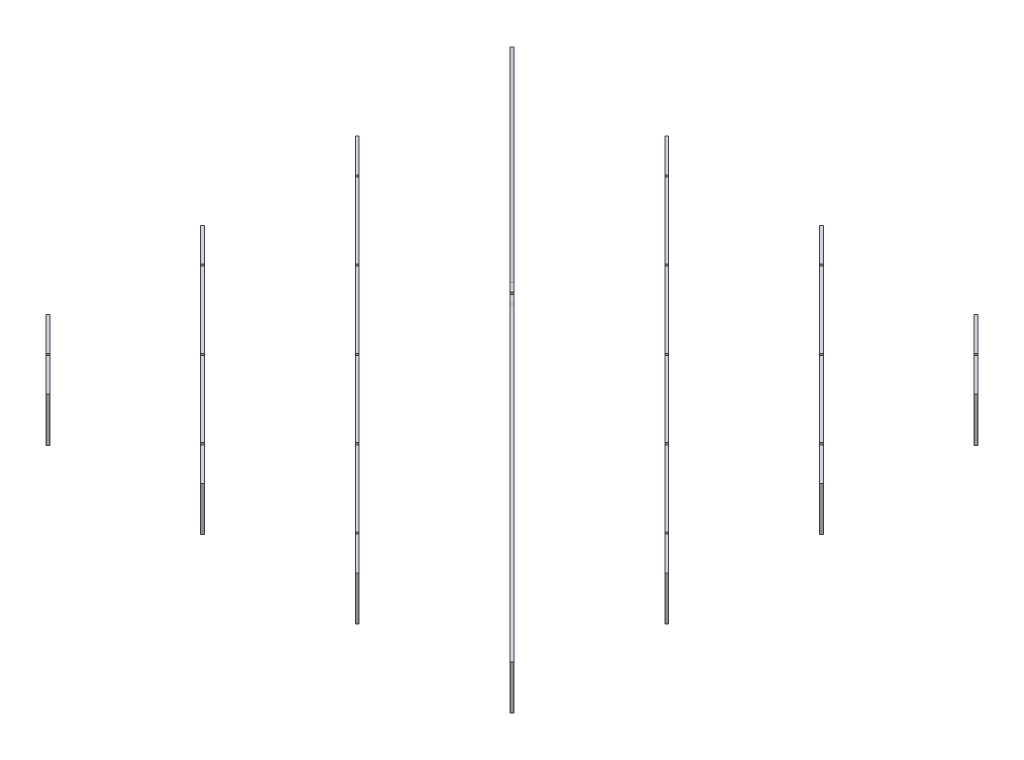
SolidWorks part; units mm, degrees
material "Plain Carbon Steel"
ref_plane "Front" through (0, 0, 0) normal (0, 0, 1) x (1, 0, 0)
ref_plane "Top" through (0, 0, 0) normal (0, 1, 0) x (1, 0, 0)
ref_plane "Right" through (0, 0, 0) normal (1, 0, 0) x (0, 0, -1)
sketch "Sketch1" plane through (0, 0, 0) normal (0, 1, 0) x (1, 0, 0)
  line L0 (-525, -525) -> (-525, 525) construction
  line L1 (-605, 605) -> (605, 605) construction
  line L2 (-605, 605) -> (-605, -605) construction
  line L3 (-605, -605) -> (605, -605) construction
  line L4 (605, 605) -> (605, -605) construction
  line L5 (-605, 605) -> (605, -605) construction
  line L6 (-605, -605) -> (605, 605) construction
  line L7 (-525, 525) -> (525, 525) construction
  line L8 (-525, 350) -> (525, 350) construction
  line L9 (-525, 175) -> (525, 175) construction
  line L10 (-525, 0) -> (525, 0) construction
  line L11 (-525, -175) -> (525, -175) construction
  line L12 (-525, -350) -> (525, -350) construction
  line L13 (-525, -525) -> (525, -525) construction
  line L14 (-350, -525) -> (-350, 525) construction
  line L15 (-175, -525) -> (-175, 525) construction
  line L16 (0, -525) -> (0, 525) construction
  line L17 (175, -525) -> (175, 525) construction
  line L18 (350, -525) -> (350, 525) construction
  line L19 (525, -525) -> (525, 525) construction
  point P0 (0, 0)
  dimension "D1" = 1210
  dimension "D2" = 1210
  dimension "D5" = 175
  dimension "D3" = 7
  dimension "D4" = 7
sketch "Sketch2" plane through (0, 0, 0) normal (0, 1, 0) x (1, 0, 0)
  line L0 (-605, 605) -> (605, -605) construction
  line L1 (602.8787, -602.8787) -> (-602.8787, -602.8787) construction
  line L2 (602.8787, -602.8787) -> (602.8787, 602.8787) construction
  line L3 (602.8787, 602.8787) -> (-602.8787, 602.8787) construction
  line L4 (-602.8787, -602.8787) -> (-602.8787, 602.8787) construction
  line L5 (602.8787, -602.8787) -> (-602.8787, 602.8787) construction
  line L6 (602.8787, 602.8787) -> (-602.8787, -602.8787) construction
  line L7 (-252.8787, 602.8787) -> (602.8787, -252.8787) construction
  line L8 (97.1213, 602.8787) -> (602.8787, 97.1213) construction
  line L9 (447.1213, 602.8787) -> (602.8787, 447.1213) construction
  line L10 (-602.8787, 252.8787) -> (252.8787, -602.8787) construction
  line L11 (-602.8787, -97.1213) -> (-97.1213, -602.8787) construction
  line L12 (-602.8787, -447.1213) -> (-447.1213, -602.8787) construction
  line L13 (-605, -449.2426) -> (-449.2426, -605)
  line L14 (-605, -99.2426) -> (-99.2426, -605)
  line L15 (-605, 250.7574) -> (250.7574, -605)
  line L16 (605, -600.7574) -> (-600.7574, 605)
  line L17 (-255, 600.7574) -> (600.7574, -255)
  line L18 (95, 600.7574) -> (600.7574, 95)
  line L19 (445, 600.7574) -> (600.7574, 445)
  line L20 (-600.7574, -445) -> (-445, -600.7574)
  line L21 (-600.7574, -95) -> (-95, -600.7574)
  line L22 (-600.7574, 255) -> (255, -600.7574)
  line L23 (600.7574, -605) -> (-605, 600.7574)
  line L24 (-250.7574, 605) -> (605, -250.7574)
  line L25 (99.2426, 605) -> (605, 99.2426)
  line L26 (449.2426, 605) -> (605, 449.2426)
  line L27 (-605, 605) -> (605, 605) construction
  line L29 (-605, -449.2426) -> (-600.7574, -445)
  line L30 (-449.2426, -605) -> (-445, -600.7574)
  line L31 (-605, -99.2426) -> (-600.7574, -95)
  line L32 (-99.2426, -605) -> (-95, -600.7574)
  line L33 (-605, 250.7574) -> (-600.7574, 255)
  line L34 (250.7574, -605) -> (255, -600.7574)
  line L35 (605, -600.7574) -> (600.7574, -605)
  line L36 (-600.7574, 605) -> (-605, 600.7574)
  line L37 (-255, 600.7574) -> (-250.7574, 605)
  line L38 (600.7574, -255) -> (605, -250.7574)
  line L39 (95, 600.7574) -> (99.2426, 605)
  line L40 (600.7574, 95) -> (605, 99.2426)
  line L41 (445, 600.7574) -> (449.2426, 605)
  line L42 (600.7574, 445) -> (605, 449.2426)
  point P0 (0, 0)
extrude "Boss-Extrude1" add sketch "Sketch2" along normal blind 100
sketch "Sketch4" plane through (-2.1213, 0, 2.1213) normal (-0.7071, 0, 0.7071) x (0.7071, 0, 0.7071)
  line L0 (0, 100) -> (0, 220) construction
  line L1 (-110.1371, 100) -> (110.1371, 100) construction
  line L2 (-30, 220) -> (-852.5992, 100)
  line L3 (-852.5992, 100) -> (-30, 100)
  line L4 (-30, 100) -> (-30, 220) construction
  line L5 (30, 220) -> (-30, 220)
  line L6 (852.5992, 100) -> (30, 100)
  line L7 (30, 220) -> (852.5992, 100)
  line L8 (-30, 100) -> (30, 100)
  dimension "D1" = 120
  dimension "D2" = 30
extrude "Boss-Extrude2" add sketch "Sketch4" against normal up to vertex
sketch "Sketch5" plane through (-527.1213, 0, 527.1213) normal (-0.7071, 0, 0.7071) x (0.7071, 0, 0.7071)
  line L0 (0, 0) -> (0, 100) construction
  line L1 (-110.1371, 100) -> (110.1371, 100) construction
  line L2 (-247.4874, 0) -> (-247.4874, 100) construction
  line L3 (494.9747, 0) -> (-247.4874, 0) construction
  line L4 (-742.4621, 0) -> (0, 0) construction
  line L5 (-357.6245, 100) -> (357.6245, 100) construction
  line L6 (-494.9747, 0) -> (-494.9747, 100) construction
  line L7 (247.4874, 0) -> (-494.9747, 0) construction
  line L8 (123.7437, 0) -> (-618.7184, 0) construction
  line L9 (-605.1118, 100) -> (605.1118, 100) construction
  line L10 (497.9747, 50) -> (491.9747, 150) construction
  line L11 (-250.4874, 150) -> (-244.4874, 150)
  line L12 (-250.4874, 150) -> (-250.4874, 50)
  line L13 (-250.4874, 50) -> (-244.4874, 50)
  line L14 (-244.4874, 150) -> (-244.4874, 50)
  line L15 (-250.4874, 150) -> (-244.4874, 50) construction
  line L16 (-250.4874, 50) -> (-244.4874, 150) construction
  line L17 (-497.9747, 150) -> (-491.9747, 150)
  line L18 (-497.9747, 150) -> (-497.9747, 50)
  line L19 (-497.9747, 50) -> (-491.9747, 50)
  line L20 (-491.9747, 150) -> (-491.9747, 50)
  line L21 (-497.9747, 150) -> (-491.9747, 50) construction
  line L22 (-497.9747, 50) -> (-491.9747, 150) construction
  line L23 (-3, 150) -> (3, 150)
  line L24 (-3, 150) -> (-3, 50)
  line L25 (-3, 50) -> (3, 50)
  line L26 (3, 150) -> (3, 50)
  line L27 (-3, 150) -> (3, 50) construction
  line L28 (-3, 50) -> (3, 150) construction
  line L29 (497.9747, 150) -> (491.9747, 50) construction
  line L30 (250.4874, 50) -> (244.4874, 150) construction
  line L31 (250.4874, 150) -> (244.4874, 50) construction
  line L32 (494.9747, 0) -> (494.9747, 100) construction
  line L33 (247.4874, 0) -> (247.4874, 100) construction
  line L34 (491.9747, 150) -> (491.9747, 50)
  line L35 (497.9747, 50) -> (491.9747, 50)
  line L36 (497.9747, 150) -> (497.9747, 50)
  line L37 (497.9747, 150) -> (491.9747, 150)
  line L38 (244.4874, 150) -> (244.4874, 50)
  line L39 (250.4874, 50) -> (244.4874, 50)
  line L40 (250.4874, 150) -> (250.4874, 50)
  line L41 (250.4874, 150) -> (244.4874, 150)
  circle A0 centre (-497.9747, 50) radius 1.5
  circle A1 centre (-491.9747, 50) radius 1.5
  circle A2 centre (-250.4874, 50) radius 1.5
  circle A3 centre (-244.4874, 50) radius 1.5
  circle A4 centre (-3, 50) radius 1.5
  circle A5 centre (3, 50) radius 1.5
  circle A6 centre (244.4874, 50) radius 1.5
  circle A7 centre (250.4874, 50) radius 1.5
  circle A8 centre (491.9747, 50) radius 1.5
  circle A9 centre (497.9747, 50) radius 1.5
  line M11 (110.1371, 100) -> (-110.1371, 100)
  dimension "D7" = 3
  dimension "D8" = 3
  dimension "D9" = 3
  dimension "D10" = 3
  dimension "D11" = 3
  dimension "D12" = 3
  dimension "D1" = 3
  dimension "D2" = 3
  dimension "D3" = 3
  dimension "D4" = 100
  dimension "D5" = 100
  dimension "D6" = 100
extrude "Cut-Extrude1" cut sketch "Sketch5" against normal up to surface (500.9747 mm away) contours L35 A9 L36 L37 L34 A8 | A8 L34 L35 | A8 L35 L34 | A9 L36 L35 | A9 L35 L36 | L39 A7 L40 L41 L38 A6 | A6 L38 L39 | A6 L39 L38 | A7 L39 L40 | A7 L40 L39 | A5 L26 L24 A4 L25 M11 | L25 A4 L24 | L24 A4 L25 | L26 A5 L25 | L25 A5 L26 | A3 L14 L11 L12 A2 L13 | L13 A2 L12 | L12 A2 L13 | L14 A3 L13 | L13 A3 L14 | A1 L20 L17 L18 A0 L19 | L19 A0 L18 | L18 A0 L19 | L20 A1 L19 | L19 A1 L20 up to face at (-172.8787, 50, 172.8787)
sketch "Sketch6" plane through (527.1213, 0, -527.1213) normal (0.7071, 0, -0.7071) x (-0.7071, 0, -0.7071)
  line L4 (-110.1371, 0) -> (110.1371, 0)
  line L5 (110.1371, 0) -> (110.1371, 100)
  line L6 (110.1371, 100) -> (-110.1371, 100)
  line L7 (-110.1371, 100) -> (-110.1371, 0)
  line L8 (-110.1371, 0) -> (110.1371, 0)
  line L9 (110.1371, 0) -> (110.1371, 100)
  line L10 (110.1371, 100) -> (-110.1371, 100)
  line L11 (-110.1371, 100) -> (-110.1371, 0)
  line L12 (497.9747, 150) -> (491.9747, 150)
  line L13 (491.9747, 150) -> (491.9747, 50)
  line L14 (491.9747, 50) -> (497.9747, 50)
  line L15 (497.9747, 50) -> (497.9747, 150)
  line L16 (497.9747, 150) -> (491.9747, 150)
  line L17 (491.9747, 150) -> (491.9747, 50)
  line L18 (491.9747, 50) -> (497.9747, 50)
  line L19 (497.9747, 50) -> (497.9747, 150)
  line L20 (250.4874, 150) -> (244.4874, 150)
  line L21 (244.4874, 150) -> (244.4874, 50)
  line L22 (244.4874, 50) -> (250.4874, 50)
  line L23 (250.4874, 50) -> (250.4874, 150)
  line L24 (250.4874, 150) -> (244.4874, 150)
  line L25 (244.4874, 150) -> (244.4874, 50)
  line L26 (244.4874, 50) -> (250.4874, 50)
  line L27 (250.4874, 50) -> (250.4874, 150)
  line L28 (-244.4874, 50) -> (-244.4874, 150)
  line L29 (-250.4874, 50) -> (-244.4874, 50)
  line L30 (-250.4874, 150) -> (-250.4874, 50)
  line L31 (-244.4874, 150) -> (-250.4874, 150)
  line L32 (-244.4874, 50) -> (-244.4874, 150)
  line L33 (-250.4874, 50) -> (-244.4874, 50)
  line L34 (-250.4874, 150) -> (-250.4874, 50)
  line L35 (-244.4874, 150) -> (-250.4874, 150)
  line L36 (-491.9747, 50) -> (-491.9747, 150)
  line L37 (-497.9747, 50) -> (-491.9747, 50)
  line L38 (-497.9747, 150) -> (-497.9747, 50)
  line L39 (-491.9747, 150) -> (-497.9747, 150)
  line L40 (-491.9747, 50) -> (-491.9747, 150)
  line L41 (-497.9747, 50) -> (-491.9747, 50)
  line L42 (-497.9747, 150) -> (-497.9747, 50)
  line L43 (-491.9747, 150) -> (-497.9747, 150)
  line L44 (3, 150) -> (-3, 150)
  line L45 (3, 50) -> (3, 150)
  line L46 (-3, 50) -> (3, 50)
  line L47 (-3, 150) -> (-3, 50)
  line L48 (3, 150) -> (-3, 150)
  line L49 (3, 50) -> (3, 150)
  line L50 (-3, 50) -> (3, 50)
  line L51 (-3, 150) -> (-3, 50)
  circle A1 centre (-3, 50) radius 1.5
  circle A2 centre (-3, 50) radius 1.5
  circle A3 centre (3, 50) radius 1.5
  circle A4 centre (3, 50) radius 1.5
  circle A5 centre (244.4874, 50) radius 1.5
  circle A6 centre (244.4874, 50) radius 1.5
  circle A7 centre (250.4874, 50) radius 1.5
  circle A8 centre (250.4874, 50) radius 1.5
  circle A9 centre (491.9747, 50) radius 1.5
  circle A10 centre (491.9747, 50) radius 1.5
  circle A11 centre (497.9747, 50) radius 1.5
  circle A12 centre (497.9747, 50) radius 1.5
  circle A13 centre (-497.9747, 50) radius 1.5
  circle A14 centre (-497.9747, 50) radius 1.5
  circle A15 centre (-491.9747, 50) radius 1.5
  circle A16 centre (-491.9747, 50) radius 1.5
  circle A17 centre (-250.4874, 50) radius 1.5
  circle A18 centre (-250.4874, 50) radius 1.5
  circle A19 centre (-244.4874, 50) radius 1.5
  circle A20 centre (-244.4874, 50) radius 1.5
  dimension "D1" = 0
  dimension "D2" = 0
  dimension "D3" = 0
  dimension "D4" = 0
  dimension "D5" = 0
  dimension "D6" = 0
  dimension "D7" = 0
  dimension "D8" = 0
  dimension "D9" = 0
  dimension "D10" = 0
  dimension "D11" = 0
  dimension "D12" = 0
  dimension "D13" = 0
  dimension "D14" = 0
  dimension "D15" = 0
  dimension "D16" = 0
extrude "Cut-Extrude2" cut sketch "Sketch6" against normal up to surface (500.9747 mm away) contours A16 L40 L43 L42 A14 L41 | L41 A14 L42 | L42 A14 L41 | L40 A16 L41 | L41 A16 L40 | A20 L32 L35 L34 A18 L33 | L33 A18 L34 | L34 A18 L33 | L32 A20 L33 | L33 A20 L32 | A4 L49 L10 L51 A2 L50 | L49 A4 L50 | L50 A4 L49 | L50 A2 L51 | L51 A2 L50 | L25 A6 L26 | L26 A6 L25 | A8 L27 L24 L25 A6 L26 | L27 A8 L26 | L26 A8 L27 | L17 A10 L18 | L18 A10 L17 | A12 L19 L16 L17 A10 L18 | L19 A12 L18 | L18 A12 L19 up to face at (172.8787, 50, -172.8787)
sketch "Sketch7" plane through (-2.1213, 0, 2.1213) normal (-0.7071, 0, 0.7071) x (0.7071, 0, 0.7071)
  line L0 (0, 220) -> (0, 0) construction
  line L1 (30, 220) -> (-30, 220) construction
  line L2 (123.7437, 0) -> (-618.7184, 0) construction
  line L3 (-3, 330) -> (3, 330)
  line L4 (-3, 330) -> (-3, 110)
  line L5 (-3, 110) -> (3, 110)
  line L6 (3, 330) -> (3, 110)
  line L7 (-3, 330) -> (3, 110) construction
  line L8 (-3, 110) -> (3, 330) construction
  line L9 (-250.4874, 50) -> (-244.4874, 50)
  line L10 (-250.4874, 50) -> (-250.4874, -50)
  line L11 (-250.4874, -50) -> (-244.4874, -50)
  line L12 (-244.4874, 50) -> (-244.4874, -50)
  line L13 (-250.4874, 50) -> (-244.4874, -50) construction
  line L14 (-250.4874, -50) -> (-244.4874, 50) construction
  line L15 (247.4874, 0) -> (-494.9747, 0) construction
  line L16 (-497.9747, 50) -> (-491.9747, 50)
  line L17 (-497.9747, 50) -> (-497.9747, -50)
  line L18 (-497.9747, -50) -> (-491.9747, -50)
  line L19 (-491.9747, 50) -> (-491.9747, -50)
  line L20 (-497.9747, 50) -> (-491.9747, -50) construction
  line L21 (-497.9747, -50) -> (-491.9747, 50) construction
  line L22 (-855.5992, 0) -> (855.5992, 0) construction
  line L23 (-742.4621, 0) -> (0, 0) construction
  line L24 (-745.4621, 50) -> (-739.4621, 50)
  line L25 (-745.4621, 50) -> (-745.4621, -50)
  line L26 (-745.4621, -50) -> (-739.4621, -50)
  line L27 (-739.4621, 50) -> (-739.4621, -50)
  line L28 (-745.4621, 50) -> (-739.4621, -50) construction
  line L29 (-745.4621, -50) -> (-739.4621, 50) construction
  line L30 (745.4621, -50) -> (739.4621, 50) construction
  line L31 (745.4621, 50) -> (739.4621, -50) construction
  line L32 (497.9747, -50) -> (491.9747, 50) construction
  line L33 (497.9747, 50) -> (491.9747, -50) construction
  line L34 (250.4874, -50) -> (244.4874, 50) construction
  line L35 (250.4874, 50) -> (244.4874, -50) construction
  line L36 (739.4621, 50) -> (739.4621, -50)
  line L37 (745.4621, -50) -> (739.4621, -50)
  line L38 (745.4621, 50) -> (745.4621, -50)
  line L39 (745.4621, 50) -> (739.4621, 50)
  line L40 (491.9747, 50) -> (491.9747, -50)
  line L41 (497.9747, -50) -> (491.9747, -50)
  line L42 (497.9747, 50) -> (497.9747, -50)
  line L43 (497.9747, 50) -> (491.9747, 50)
  line L44 (244.4874, 50) -> (244.4874, -50)
  line L45 (250.4874, -50) -> (244.4874, -50)
  line L46 (250.4874, 50) -> (250.4874, -50)
  line L47 (250.4874, 50) -> (244.4874, 50)
  circle A0 centre (-3, 110) radius 1.5
  circle A1 centre (3, 110) radius 1.5
  circle A2 centre (-250.4874, 50) radius 1.5
  circle A3 centre (-244.4874, 50) radius 1.5
  circle A4 centre (-491.9747, 50) radius 1.5
  circle A5 centre (-497.9747, 50) radius 1.5
  circle A6 centre (-739.4621, 50) radius 1.5
  circle A7 centre (-745.4621, 50) radius 1.5
  circle A8 centre (745.4621, 50) radius 1.5
  circle A9 centre (739.4621, 50) radius 1.5
  circle A10 centre (497.9747, 50) radius 1.5
  circle A11 centre (491.9747, 50) radius 1.5
  circle A12 centre (244.4874, 50) radius 1.5
  circle A13 centre (250.4874, 50) radius 1.5
  point P9 (-247.4874, 0)
  point P16 (-494.9747, 0)
  point P25 (-742.4621, 0)
  point P32 (0, 110)
  point P59 (742.4621, 0)
  point P60 (494.9747, 0)
  point P61 (247.4874, 0)
  line M15 (-852.5992, 0) -> (852.5992, 0)
  line M18 (30, 220) -> (-30, 220)
  dimension "D7" = 3
  dimension "D8" = 3
  dimension "D9" = 3
  dimension "D10" = 3
  dimension "D11" = 3
  dimension "D12" = 3
  dimension "D1" = 3
  dimension "D3" = 3
  dimension "D4" = 100
  dimension "D6" = 100
  dimension "D13" = 3
  dimension "D14" = 3
  dimension "D15" = 3
  dimension "D2" = 100
  dimension "D5" = 3
extrude "Cut-Extrude3" cut sketch "Sketch7" against normal up to next (6 mm away) contours L24 A7 L25 | L25 A7 L24 | A7 L25 L27 A6 L24 M15 | L24 A6 L27 | L27 A6 L24 | L16 A5 L17 | L17 A5 L16 | A5 L17 L19 A4 L16 M15 | L16 A4 L19 | L19 A4 L16 | L12 A3 L9 | L9 A3 L12 | A3 L9 A2 L10 L12 M15 | L10 A2 L9 | L9 A2 L10 | A1 L6 L4 A0 L5 M18 | L5 A0 L4 | L4 A0 L5 | L5 A1 L6 | L6 A1 L5 | A12 L44 L47 | A12 L47 L44 | L46 A13 L47 A12 L44 M15 | A13 L46 L47 | A13 L47 L46 | A11 L40 L43 | A11 L43 L40 | L43 A11 L40 L42 A10 M15 | A10 L42 L43 | A10 L43 L42 | A9 L36 L39 | A9 L39 L36 | L39 A9 L36 L38 A8 M15 | A8 L38 L39 | A8 L39 L38
sketch "Sketch8" plane through (-2.1213, 0, 2.1213) normal (-0.7071, 0, 0.7071) x (0.7071, 0, 0.7071)
  line L0 (346.2311, 22) -> (396.2311, 22) construction
  line L1 (346.2311, 19) -> (346.2311, 25) construction
  line L2 (396.2311, 25) -> (396.2311, 19) construction
  line L3 (371.2311, 25) -> (371.2311, 19) construction
  line L4 (386.2311, 25) -> (356.2311, 25) construction
  line L5 (356.2311, 19) -> (386.2311, 19) construction
  line L6 (0, 0) -> (0, 262.5502) construction
  line L7 (343.2311, 28) -> (399.2311, 28)
  line L8 (343.2311, 28) -> (343.2311, 16)
  line L9 (343.2311, 16) -> (399.2311, 16)
  line L10 (399.2311, 28) -> (399.2311, 16)
  line L11 (343.2311, 28) -> (399.2311, 16) construction
  line L12 (343.2311, 16) -> (399.2311, 28) construction
  line L13 (-343.2311, 16) -> (-399.2311, 28) construction
  line L14 (-343.2311, 28) -> (-399.2311, 16) construction
  line L15 (-371.2311, 25) -> (-371.2311, 19) construction
  line L16 (-346.2311, 22) -> (-396.2311, 22) construction
  line L17 (-399.2311, 28) -> (-399.2311, 16)
  line L18 (-343.2311, 16) -> (-399.2311, 16)
  line L19 (-343.2311, 28) -> (-343.2311, 16)
  line L20 (-343.2311, 28) -> (-399.2311, 28)
  point P12 (371.2311, 22)
  point P28 (-371.2311, 22)
  dimension "D1" = 3
  dimension "D2" = 3
extrude "Cut-Extrude4" cut sketch "Sketch8" against normal up to next (6 mm away)
sketch "Sketch9" plane through (2.1213, 0, -2.1213) normal (0.7071, 0, -0.7071) x (-0.7071, 0, -0.7071)
  line L0 (123.7437, 74) -> (-123.7437, 74) construction
  line L1 (0, 0) -> (0, 292.3791) construction
  circle A0 centre (123.7437, 64) radius 4
  circle A1 centre (123.7437, 84) radius 4
  circle A2 centre (40, 74) radius 10
  circle A3 centre (-40, 74) radius 10
  circle A4 centre (-123.7437, 84) radius 4
  circle A5 centre (-123.7437, 64) radius 4
  dimension "D1" = 8
  dimension "D2" = 20
  dimension "D3" = 80
extrude "Cut-Extrude5" cut sketch "Sketch9" against normal up to next (6 mm away)
sketch "Sketch10" plane through (177.1213, 0, -177.1213) normal (0.7071, 0, -0.7071) x (-0.7071, 0, -0.7071)
  line L0 (371.2311, 100) -> (371.2311, 0) construction
  line L1 (250.4874, 100) -> (491.9747, 100) construction
  line L2 (-605.1118, 0) -> (605.1118, 0) construction
  line L3 (123.7437, 100) -> (123.7437, 0) construction
  line L4 (3, 100) -> (244.4874, 100) construction
  line L5 (-123.7437, 100) -> (-123.7437, 0) construction
  line L6 (-244.4874, 100) -> (-3, 100) construction
  line L7 (-371.2311, 100) -> (-371.2311, 0) construction
  line L8 (-491.9747, 100) -> (-250.4874, 100) construction
  circle A0 centre (371.2311, 50) radius 3
  circle A1 centre (123.7437, 50) radius 3
  circle A2 centre (-123.7437, 50) radius 3
  circle A3 centre (-371.2311, 50) radius 3
  dimension "D1" = 6
extrude "Cut-Extrude6" cut sketch "Sketch10" along normal up to surface (253.4874 mm away) from surface at -6 up to face at (352.1213, 63.5516, -352.1213) starting at face at (172.8787, 64.6145, -172.8787)
ref_plane "Plane1" through (0, 0, 0) normal (0.7071, 0, -0.7071) x (-0.7071, 0, -0.7071)
mirror "Mirror1" about plane through (0, 0, 0) normal (0.7071, 0, -0.7071) of "Cut-Extrude6"
equation "\"D1@Boss-Extrude1\"=\"Plate width\""
equation "\"Plate width\"=100"
equation "\"D1@Sketch5\"=\"Half rib thickness\""
equation "\"D2@Sketch5\"=\"Half rib thickness\""
equation "\"D3@Sketch5\"=\"Half rib thickness\""
equation "\"D4@Sketch5\"=\"Plate width\""
equation "\"D5@Sketch5\"=\"Plate width\""
equation "\"D6@Sketch5\"=\"Plate width\""
equation "\"D7@Sketch5\"=\"Half rib thickness\""
equation "\"D8@Sketch5\"=\"Half rib thickness\""
equation "\"D9@Sketch5\"=\"Half rib thickness\""
equation "\"D10@Sketch5\"=\"Half rib thickness\""
equation "\"D11@Sketch5\"=\"Half rib thickness\""
equation "\"D12@Sketch5\"=\"Half rib thickness\""
equation "\"D1@Sketch7\"=\"Half rib thickness\""
equation "\"D2@Sketch7\"=\"Plate width\""
equation "\"D3@Sketch7\"=\"Half rib thickness\""
equation "\"D4@Sketch7\"=\"Plate width\""
equation "\"D5@Sketch7\"=\"Half rib thickness\""
equation "\"D6@Sketch7\"=\"Plate width\""
equation "\"D7@Sketch7\"=\"Half rib thickness\""
equation "\"D8@Sketch7\"=\"Half rib thickness\""
equation "\"D9@Sketch7\"=\"Half rib thickness\""
equation "\"D10@Sketch7\"=\"Half rib thickness\""
equation "\"D11@Sketch7\"=\"Half rib thickness\""
equation "\"D12@Sketch7\"=\"Half rib thickness\""
equation "\"D13@Sketch7\"=\"Half rib thickness\""
equation "\"D14@Sketch7\"=\"Half rib thickness\""
equation "\"D15@Sketch7\"=\"Half rib thickness\""
